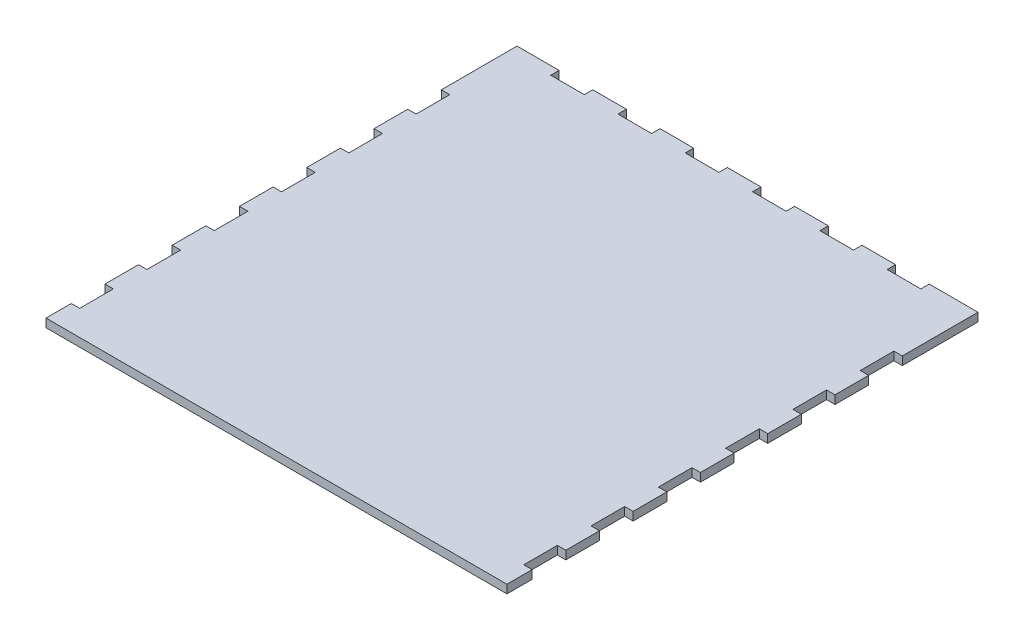
SolidWorks part; units mm, degrees
ref_plane "Front Plane" through (0, 0, 0) normal (0, 0, 1) x (1, 0, 0)
ref_plane "Top Plane" through (0, 0, 0) normal (0, 1, 0) x (1, 0, 0)
ref_plane "Right Plane" through (0, 0, 0) normal (1, 0, 0) x (0, 0, -1)
sketch "Sketch1" plane through (0, 0, 0) normal (0, 1, 0) x (1, 0, 0)
  line L1 (86.995, -88.9) -> (-86.995, -88.9)
  line L2 (86.995, -88.9) -> (86.995, 88.9)
  line L3 (86.995, 88.9) -> (-86.995, 88.9)
  line L4 (-86.995, -88.9) -> (-86.995, 88.9)
  line L5 (86.995, -88.9) -> (-86.995, 88.9) construction
  line L6 (86.995, 88.9) -> (-86.995, -88.9) construction
  point P0 (0, 0)
  dimension "D1" = 173.99
  dimension "D2" = 177.8
extrude "Boss-Extrude1" add sketch "Sketch1" along normal blind 3.175
sketch "Sketch3" plane through (0, 3.175, 0) normal (0, 1, 0) x (1, 0, 0)
  line L0 (86.995, 88.9) -> (-86.995, 88.9) construction
  line L1 (-71.12, 88.9) -> (-58.42, 88.9)
  line L2 (-71.12, 88.9) -> (-71.12, 85.725)
  line L3 (-71.12, 85.725) -> (-58.42, 85.725)
  line L4 (-58.42, 88.9) -> (-58.42, 85.725)
  line L5 (-86.995, 88.9) -> (-86.995, -88.9) construction
  line L6 (-45.72, 88.9) -> (-45.72, 85.725)
  line L7 (-45.72, 88.9) -> (-33.02, 88.9)
  line L8 (-33.02, 88.9) -> (-33.02, 85.725)
  line L9 (-45.72, 85.725) -> (-33.02, 85.725)
  line L10 (-20.32, 88.9) -> (-20.32, 85.725)
  line L11 (-20.32, 88.9) -> (-7.62, 88.9)
  line L12 (-7.62, 88.9) -> (-7.62, 85.725)
  line L13 (-20.32, 85.725) -> (-7.62, 85.725)
  line L14 (5.08, 88.9) -> (5.08, 85.725)
  line L15 (5.08, 88.9) -> (17.78, 88.9)
  line L16 (17.78, 88.9) -> (17.78, 85.725)
  line L17 (5.08, 85.725) -> (17.78, 85.725)
  line L18 (30.48, 88.9) -> (30.48, 85.725)
  line L19 (30.48, 88.9) -> (43.18, 88.9)
  line L20 (43.18, 88.9) -> (43.18, 85.725)
  line L21 (30.48, 85.725) -> (43.18, 85.725)
  line L22 (55.88, 88.9) -> (55.88, 85.725)
  line L23 (55.88, 88.9) -> (68.58, 88.9)
  line L24 (68.58, 88.9) -> (68.58, 85.725)
  line L25 (55.88, 85.725) -> (68.58, 85.725)
  line L26 (-86.995, 34.925) -> (-86.995, 22.225)
  line L27 (-86.995, 60.325) -> (-83.82, 60.325)
  line L28 (-86.995, 60.325) -> (-86.995, 47.625)
  line L29 (-86.995, 47.625) -> (-83.82, 47.625)
  line L30 (-83.82, 60.325) -> (-83.82, 47.625)
  line L31 (-86.995, 34.925) -> (-83.82, 34.925)
  line L32 (-83.82, 34.925) -> (-83.82, 22.225)
  line L33 (-86.995, 22.225) -> (-83.82, 22.225)
  line L34 (-86.995, 9.525) -> (-86.995, -3.175)
  line L35 (-86.995, 9.525) -> (-83.82, 9.525)
  line L36 (-83.82, 9.525) -> (-83.82, -3.175)
  line L37 (-86.995, -3.175) -> (-83.82, -3.175)
  line L38 (-86.995, -15.875) -> (-86.995, -28.575)
  line L39 (-86.995, -15.875) -> (-83.82, -15.875)
  line L40 (-83.82, -15.875) -> (-83.82, -28.575)
  line L41 (-86.995, -28.575) -> (-83.82, -28.575)
  line L42 (-86.995, -41.275) -> (-86.995, -53.975)
  line L43 (-86.995, -41.275) -> (-83.82, -41.275)
  line L44 (-83.82, -41.275) -> (-83.82, -53.975)
  line L45 (-86.995, -53.975) -> (-83.82, -53.975)
  line L46 (-86.995, -66.675) -> (-86.995, -79.375)
  line L47 (-86.995, -66.675) -> (-83.82, -66.675)
  line L48 (-83.82, -66.675) -> (-83.82, -79.375)
  line L49 (-86.995, -79.375) -> (-83.82, -79.375)
  line L50 (0, 0) -> (0, 92.0039) construction
  line L51 (86.995, -66.675) -> (83.82, -66.675)
  line L52 (83.82, -66.675) -> (83.82, -79.375)
  line L53 (86.995, -79.375) -> (83.82, -79.375)
  line L54 (86.995, -66.675) -> (86.995, -79.375)
  line L55 (86.995, -41.275) -> (83.82, -41.275)
  line L56 (83.82, -41.275) -> (83.82, -53.975)
  line L57 (86.995, -53.975) -> (83.82, -53.975)
  line L58 (86.995, -41.275) -> (86.995, -53.975)
  line L59 (86.995, -15.875) -> (83.82, -15.875)
  line L60 (83.82, -15.875) -> (83.82, -28.575)
  line L61 (86.995, -28.575) -> (83.82, -28.575)
  line L62 (86.995, -15.875) -> (86.995, -28.575)
  line L63 (86.995, 9.525) -> (83.82, 9.525)
  line L64 (83.82, 9.525) -> (83.82, -3.175)
  line L65 (86.995, -3.175) -> (83.82, -3.175)
  line L66 (86.995, 9.525) -> (86.995, -3.175)
  line L67 (86.995, 34.925) -> (83.82, 34.925)
  line L68 (83.82, 34.925) -> (83.82, 22.225)
  line L69 (86.995, 22.225) -> (83.82, 22.225)
  line L70 (86.995, 34.925) -> (86.995, 22.225)
  line L71 (86.995, 47.625) -> (83.82, 47.625)
  line L72 (83.82, 60.325) -> (83.82, 47.625)
  line L73 (86.995, 60.325) -> (83.82, 60.325)
  line L74 (86.995, 60.325) -> (86.995, 47.625)
  dimension "D1" = 12.7
  dimension "D2" = 15.875
  dimension "D3" = 3.175
  dimension "D5" = 12.7
  dimension "D6" = 28.575
  dimension "D7" = 3.175
  dimension "D4" = 6
  dimension "D8" = 6
extrude "Cut-Extrude1" cut sketch "Sketch3" against normal blind 3.175
